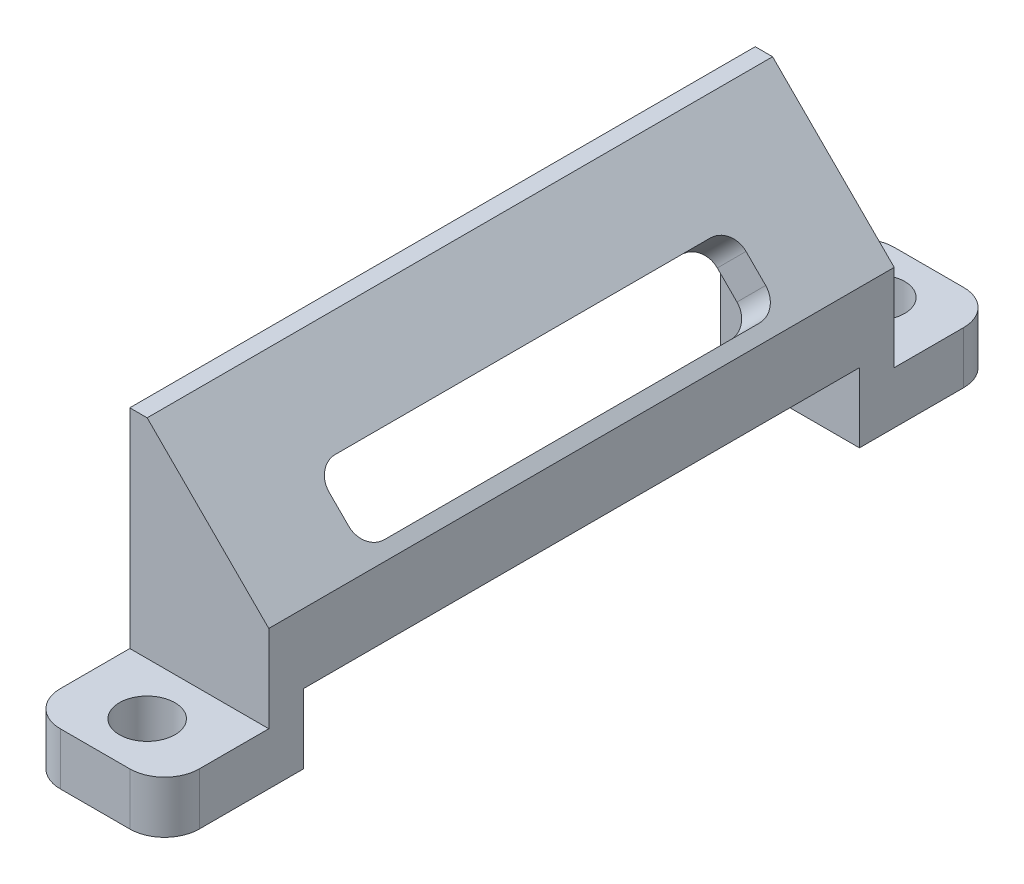
SolidWorks part; units mm, degrees
material "6061 合金"
ref_plane "前视基准面" through (0, 0, 0) normal (0, 0, 1) x (1, 0, 0)
ref_plane "上视基准面" through (0, 0, 0) normal (0, 1, 0) x (1, 0, 0)
ref_plane "右视基准面" through (0, 0, 0) normal (1, 0, 0) x (0, 0, -1)
sketch "草图1" plane through (0, 0, 0) normal (0, 0, 1) x (1, 0, 0)
  line L1 (0, 0) -> (8, 0)
  line L2 (0, 0) -> (0, 15)
  line L3 (0, 15) -> (8, 15)
  line L4 (8, 0) -> (8, 15)
  dimension "D1" = 8
  dimension "D2" = 15
extrude "凸台-拉伸1" add sketch "草图1" along normal blind 48
sketch "草图2" plane through (0, 15, 0) normal (0, 1, 0) x (1, 0, 0)
  line L1 (8, -48) -> (8, 0) construction
  line L2 (0, 0) -> (8, 0)
  line L3 (0, 0) -> (0, -6)
  line L4 (0, -6) -> (8, -6)
  line L5 (8, 0) -> (8, -6)
  line L7 (0, -48) -> (8, -48)
  line L8 (0, -48) -> (0, -42)
  line L9 (0, -42) -> (8, -42)
  line L10 (8, -48) -> (8, -42)
  dimension "D1" = 6
  dimension "D2" = 6
extrude "切除-拉伸1" cut sketch "草图2" against normal offset from surface (12 mm away) 3 up to face at (4, 0, 24)
sketch "草图4" plane through (0, 0, 0) normal (0, -1, 0) x (1, 0, 0)
  line L0 (0, 48) -> (0, 0) construction
  line L1 (0, 40) -> (8, 40)
  line L2 (0, 40) -> (0, 8)
  line L3 (0, 8) -> (8, 8)
  line L4 (8, 40) -> (8, 8)
  line L5 (8, 48) -> (8, 0) construction
  line L6 (0, 48) -> (8, 48) construction
  line L7 (0, 0) -> (8, 0) construction
  dimension "D1" = 8
  dimension "D2" = 8
extrude "切除-拉伸3" cut sketch "草图4" against normal blind 4
sketch "草图5" plane through (0, 3, 0) normal (0, 1, 0) x (1, 0, 0)
  line L0 (0, -24) -> (22.7901, -24) construction
  line L1 (0, -42) -> (0, -6) construction
  line L2 (4, 0) -> (4, -65.9599) construction
  line L4 (0, 0) -> (8, 0) construction
  circle A0 centre (4, -3) radius 1.6
  circle A1 centre (4, -45) radius 1.6
  dimension "D1" = 42
  dimension "D2" = 3.2
extrude "切除-拉伸4" cut sketch "草图5" against normal blind 3
fillet "圆角1" radius 2 4 edges at (0, 1.5, 48) (8, 1.5, 48) (0, 1.5, 0) (8, 1.5, 0)
sketch "草图3" plane through (0, 0, 40) normal (0, 0, 1) x (1, 0, 0)
  line L0 (0, 4) -> (7, 4)
  line L1 (0, 4) -> (8, 4) construction
  line L2 (7, 4) -> (0, 11)
  line L3 (0, 3) -> (0, 15) construction
  line L4 (0, 11) -> (0, 4)
  dimension "D1" = 7
  dimension "D2" = 7
extrude "切除-拉伸5" cut sketch "草图3" against normal up to surface (32 mm away) up to face at (4, 2, 8)
sketch "草图6" plane through (5.5, 5.5, 0) normal (-0.7071, -0.7071, 0) x (0, 0, 1)
  line L0 (24, 7.7782) -> (24, -13.9173) construction
  line L1 (8, 7.7782) -> (40, 7.7782) construction
  line L2 (40, -2.1213) -> (40, 7.7782) construction
  line L3 (9, 6.7782) -> (39, 6.7782)
  line L4 (9, 6.7782) -> (9, -1.2218)
  line L5 (9, -1.2218) -> (39, -1.2218)
  line L6 (39, 6.7782) -> (39, -1.2218)
  dimension "D1" = 30
  dimension "D2" = 8
  dimension "D3" = 1
  dimension "D4" = 1
extrude "切除-拉伸6" cut sketch "草图6" against normal blind 1
chamfer "倒角1" distance 7 angle 45 1 edges at (8, 15, 24)
fillet "圆角2" radius 0.8 4 edges at (1.0607, 10.6464, 39) (6.7175, 4.9896, 39) (6.7175, 4.9896, 9) (1.0607, 10.6464, 9)
sketch "草图7" plane through (6.2071, 6.2071, 0) normal (-0.7071, -0.7071, 0) x (0, 0, 1)
  line L0 (24, 6.7782) -> (24, -4.8077) construction
  line L1 (13.2, 4.7782) -> (34.8, 4.7782)
  line L2 (12, 3.5782) -> (12, 1.9782)
  line L3 (13.2, 0.7782) -> (34.8, 0.7782)
  line L4 (36, 3.5782) -> (36, 1.9782)
  line L5 (38.2, 6.7782) -> (9.8, 6.7782) construction
  line L6 (9, 2.7782) -> (26.905, 2.7782) construction
  line L7 (9, 5.9782) -> (9, -0.4218) construction
  arc A0 (36, 3.5782) -> (34.8, 4.7782) centre (34.8, 3.5782) ccw
  arc A1 (36, 1.9782) -> (34.8, 0.7782) centre (34.8, 1.9782) cw
  arc A2 (12, 1.9782) -> (13.2, 0.7782) centre (13.2, 1.9782) ccw
  arc A3 (12, 3.5782) -> (13.2, 4.7782) centre (13.2, 3.5782) cw
  point P14 (36, 4.7782)
  point P19 (12, 0.7782)
  point P22 (12, 4.7782)
  dimension "D3" = 1.2
  dimension "D1" = 24
  dimension "D2" = 4
extrude "切除-拉伸7" cut sketch "草图7" against normal blind 10
sketch "草图8" plane through (6.2071, 6.2071, 0) normal (-0.7071, -0.7071, 0) x (0, 0, 1)
  line L0 (24, 4.7782) -> (24, 1.6375) construction
  line L1 (12, 5.5282) -> (36, 5.5282)
  line L2 (11, 4.5282) -> (11, 1.0282)
  line L3 (12, 0.0282) -> (36, 0.0282)
  line L4 (37, 4.5282) -> (37, 1.0282)
  line L5 (34.8, 4.7782) -> (13.2, 4.7782) construction
  line L6 (12, 2.7782) -> (26.1149, 2.7782) construction
  line L7 (12, 3.5782) -> (12, 1.9782) construction
  arc A0 (36, 0.0282) -> (37, 1.0282) centre (36, 1.0282) ccw
  arc A1 (37, 4.5282) -> (36, 5.5282) centre (36, 4.5282) ccw
  arc A2 (11, 1.0282) -> (12, 0.0282) centre (12, 1.0282) ccw
  arc A3 (11, 4.5282) -> (12, 5.5282) centre (12, 4.5282) cw
  point P16 (37, 5.5282)
  point P19 (11, 0.0282)
  point P22 (11, 5.5282)
  dimension "D3" = 1
  dimension "D1" = 26
  dimension "D2" = 5.5
extrude "切除-拉伸8" cut sketch "草图8" against normal blind 0.2
